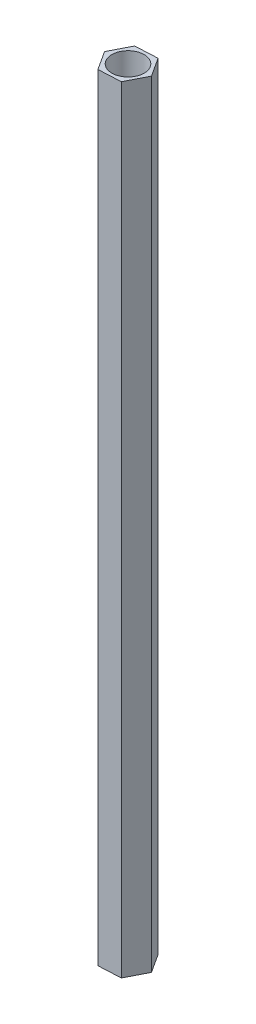
SolidWorks part; units mm, degrees
material "黄铜"
ref_plane "前视基准面" through (0, 0, 0) normal (0, 0, 1) x (1, 0, 0)
ref_plane "上视基准面" through (0, 0, 0) normal (0, 1, 0) x (1, 0, 0)
ref_plane "右视基准面" through (0, 0, 0) normal (1, 0, 0) x (0, 0, -1)
sketch "草图1" plane through (0, 0, 0) normal (0, 1, 0) x (1, 0, 0)
  line L1 (0.9409, -1.4542) -> (1.7298, 0.0878)
  line L2 (1.7298, 0.0878) -> (0.7889, 1.542)
  line L3 (0.7889, 1.542) -> (-0.9409, 1.4542)
  line L4 (-0.9409, 1.4542) -> (-1.7298, -0.0878)
  line L5 (-1.7298, -0.0878) -> (-0.7889, -1.542)
  line L6 (-0.7889, -1.542) -> (0.9409, -1.4542)
  circle A0 centre (0, 0) radius 1.5 construction
  dimension "D1" = 3
extrude "凸台-拉伸1" add sketch "草图1" along normal blind 55.63
sketch "草图2" plane through (0, 55.63, 0) normal (0, 1, 0) x (1, 0, 0)
  circle A0 centre (0, 0) radius 1.25
  dimension "D1" = 2.5
extrude "切除-拉伸1" cut sketch "草图2" against normal blind 55.63
sketch "草图3" plane through (0, 55.63, 0) normal (0, 1, 0) x (1, 0, 0)
  line L1 (0.7889, 1.542) -> (-0.9409, 1.4542)
  line L2 (-0.9409, 1.4542) -> (-1.7298, -0.0878)
  line L3 (-1.7298, -0.0878) -> (-0.7889, -1.542)
  line L4 (-0.7889, -1.542) -> (0.9409, -1.4542)
  line L5 (0.9409, -1.4542) -> (1.7298, 0.0878)
  line L6 (1.7298, 0.0878) -> (0.7889, 1.542)
  circle A0 centre (0, 0) radius 1.25
  circle A1 centre (0, 0) radius 1.5 construction
extrude "凸台-拉伸2" add sketch "草图3" along normal up to vertex (4.4903 mm away)
